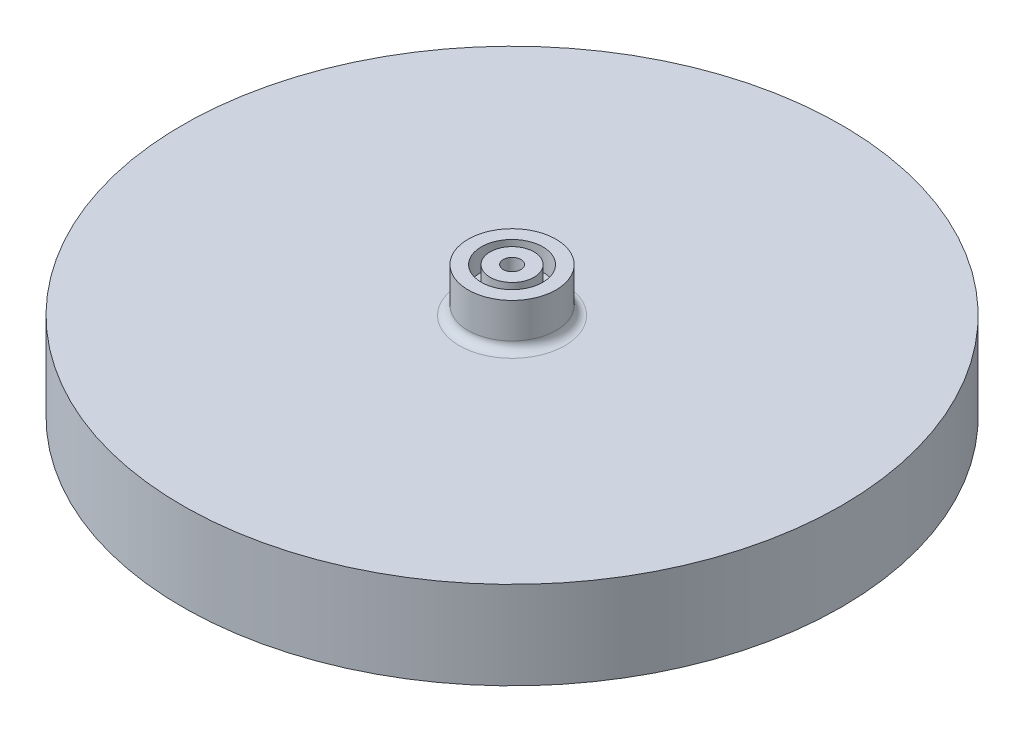
SolidWorks part; units mm, degrees
ref_plane "前视基准面" through (0, 0, 0) normal (0, 0, 1) x (1, 0, 0)
ref_plane "上视基准面" through (0, 0, 0) normal (0, 1, 0) x (1, 0, 0)
ref_plane "右视基准面" through (0, 0, 0) normal (1, 0, 0) x (0, 0, -1)
other "Configuration Table"
sketch "草图1" plane through (0, 0, 0) normal (0, 0, 1) x (1, 0, 0)
  line L0 (0, -198.1759) -> (0, 9710.6208) construction
  line L1 (0, 0) -> (-2, 0)
  line L2 (-2, 0) -> (-2, 8)
  line L3 (-2, 8) -> (-5, 8)
  line L4 (-5, 8) -> (-5, 3)
  line L5 (-5, 3) -> (-7, 3)
  line L6 (-7, 3) -> (-7, 8)
  line L7 (-7, 8) -> (-10, 8)
  line L8 (-10, 8) -> (-10, -2)
  line L9 (-10, -2) -> (-75, -2)
  line L10 (-75, -2) -> (-75, -22)
  line L11 (-75, -22) -> (0, -22)
  line L12 (0, -22) -> (0, 0)
  dimension "D1" = 20
  dimension "D2" = 5
  dimension "D3" = 3
  dimension "D4" = 3
  dimension "D5" = 8
  dimension "D6" = 4
  dimension "D7" = 150
  dimension "D8" = 20
  dimension "D9" = 2
revolve "旋转1" add sketch "草图1" angle 360 about L0
fillet "圆角1" radius 2 1 edges at (10, -2, 0)
